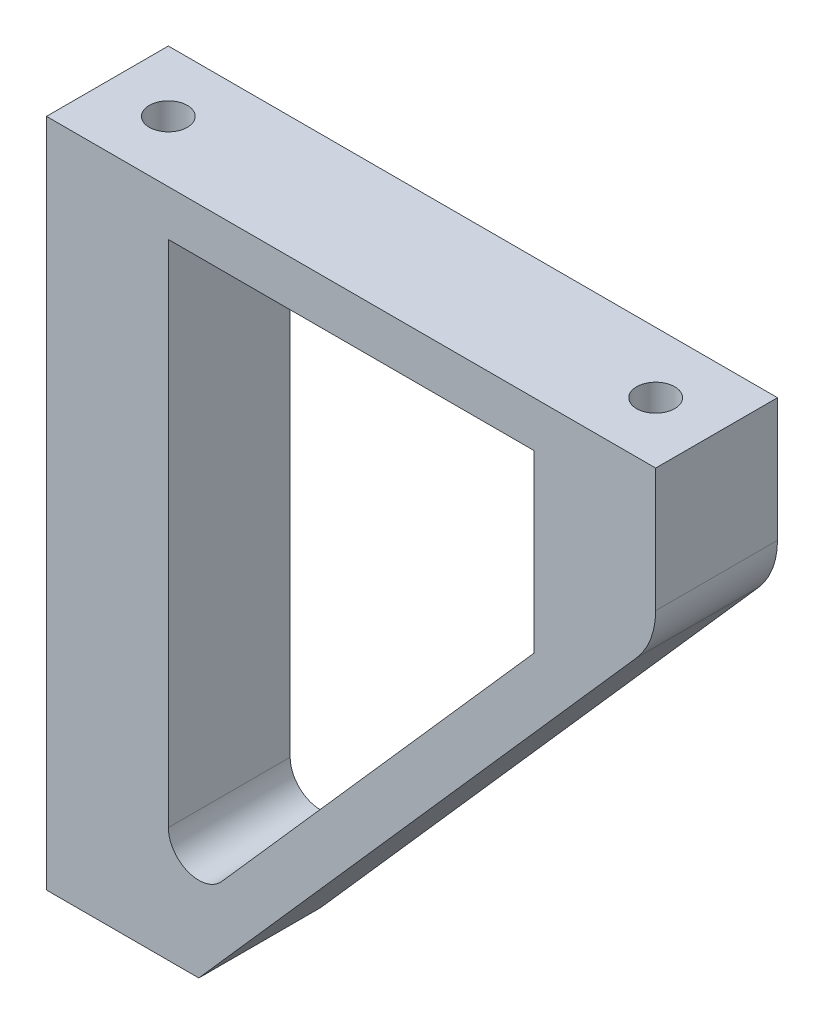
SolidWorks part; units mm, degrees
ref_plane "Спереди" through (0, 0, 0) normal (0, 0, 1) x (1, 0, 0)
ref_plane "Сверху" through (0, 0, 0) normal (0, 1, 0) x (1, 0, 0)
ref_plane "Справа" through (0, 0, 0) normal (1, 0, 0) x (0, 0, -1)
sketch "Эскиз1" plane through (0, 0, 0) normal (0, 0, 1) x (1, 0, 0)
  line L0 (-20, 22) -> (-20, -22)
  line L1 (-20, -22) -> (-10, -22)
  line L2 (-10, -22) -> (20, 12)
  line L3 (20, 12) -> (20, 22)
  line L4 (20, 22) -> (-20, 22)
  line L5 (-12, 19) -> (-12, -14.4428)
  line L7 (-8.5003, -15.7661) -> (12, 7.4676)
  line L8 (12, 7.4676) -> (12, 19)
  line L9 (12, 19) -> (-12, 19)
  line L10 (-16, 22) -> (-16, -22) construction
  line L11 (-12, 19) -> (-20, 19) construction
  line L12 (12, 19) -> (20, 19) construction
  line L13 (16, 22) -> (16, 7.4667) construction
  arc A0 (-12, -14.4428) -> (-8.5003, -15.7661) centre (-10, -14.4428) ccw
  point P1 (0, 22)
  point P6 (-20, 0)
  point P9 (0, 19)
  point P16 (-16, 19)
  point P22 (16, 19)
  dimension "D6" = 4
  dimension "D1" = 8
  dimension "D2" = 3
  dimension "D3" = 44
  dimension "D4" = 3
  dimension "D5" = 32
  dimension "D7" = 10
extrude "тело" add sketch "Эскиз1" along normal blind 8
fillet "Скругление1" [suppressed] radius 2
sketch "Эскиз5" plane through (0, -22, 0) normal (0, -1, 0) x (1, 0, 0)
  line L0 (-20, 0) -> (-10, 0) construction
  line L1 (-20, 8) -> (-12, 8) construction
  line L2 (-20, 8) -> (-20, 0) construction
  line L3 (-20, 0) -> (-12, 0) construction
  line L4 (-12, 8) -> (-12, 0) construction
  line L5 (-20, 4) -> (-12, 4) construction
  circle A0 centre (-16, 4) radius 1.25
  dimension "D1" = 2.5
extrude "отверстие под шуруп снизу" cut sketch "Эскиз5" against normal blind 13
sketch "Эскиз6" plane through (0, 22, 0) normal (0, 1, 0) x (1, 0, 0)
  line L0 (20, -8) -> (-20, -8) construction
  line L1 (20, 0) -> (12, 0) construction
  line L2 (20, 0) -> (20, -8) construction
  line L3 (20, -8) -> (12, -8) construction
  line L4 (12, 0) -> (12, -8) construction
  line L5 (12, -4) -> (20, -4) construction
  circle A0 centre (16, -4) radius 1.25
  dimension "D1" = 2.5
extrude "отверстие под шуруп сверху" cut sketch "Эскиз6" against normal blind 10
sketch "Эскиз7" [suppressed] plane through (0, 0, 0) normal (0, 0, 1) x (1, 0, 0)
  line L0 (-62.3538, 18.3615) -> (-62.3538, -16.6385)
  line L1 (-62.3538, -16.6385) -> (-51.5846, -16.6385)
  line L2 (-51.5846, -16.6385) -> (-32.8829, 7.5923)
  line L3 (-32.8829, 7.5923) -> (-32.8829, 18.3615)
  line L4 (-32.8829, 18.3615) -> (-62.3538, 18.3615)
  line L5 (-58.5846, 15.1308) -> (-58.5846, -12.1154)
  line L6 (-58.5846, -12.1154) -> (-53.0893, -12.1154)
  line L7 (-53.0893, -12.1154) -> (-39.2792, 5.7776)
  line L8 (-39.2792, 5.7776) -> (-39.2792, 15.1308)
  line L9 (-39.2792, 15.1308) -> (-58.5846, 15.1308)
  line L10 (-58.5846, 15.1308) -> (-62.3538, 15.1308) construction
  line L11 (-39.2792, 15.1308) -> (-32.8829, 15.1308) construction
  line L12 (-60.4692, 18.3615) -> (-60.4692, -16.6385) construction
  line L13 (-36.0811, 18.3615) -> (-36.0811, 3.4486) construction
  point P14 (-60.4692, 15.1308)
  point P17 (-36.0811, 15.1308)
  dimension "D1" = 35
fillet "Скругление2" radius 5 1 edges at (20, 12, 4)
mirror "Зеркальное отражение1" about plane through (0, 0, 0) normal (0, 1, 0) of "отверстие под шуруп снизу"
